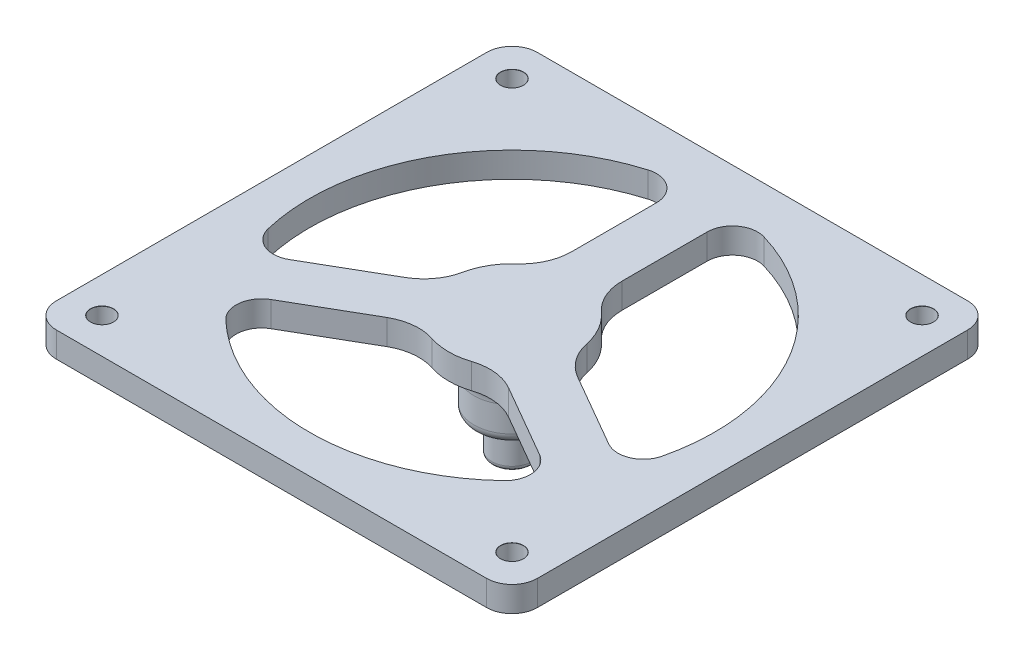
SolidWorks part; units mm, degrees
ref_plane "Front Plane" through (0, 0, 0) normal (0, 0, 1) x (1, 0, 0)
ref_plane "Top Plane" through (0, 0, 0) normal (0, 1, 0) x (1, 0, 0)
ref_plane "Right Plane" through (0, 0, 0) normal (1, 0, 0) x (0, 0, -1)
sketch "Sketch1" plane through (0, 0, 0) normal (0, 1, 0) x (1, 0, 0)
  line L1 (-47.5, -47.5) -> (47.5, -47.5)
  line L2 (-47.5, -47.5) -> (-47.5, 47.5)
  line L3 (-47.5, 47.5) -> (47.5, 47.5)
  line L4 (47.5, -47.5) -> (47.5, 47.5)
  line L5 (-47.5, -47.5) -> (47.5, 47.5) construction
  line L6 (-47.5, 47.5) -> (47.5, -47.5) construction
  point P0 (0, 0)
  dimension "D1" = 95
extrude "Boss-Extrude1" add sketch "Sketch1" along normal blind 5 contours L2 L3 L4 L1
fillet "Fillet1" radius 5 4 edges at (-47.5, 2.5, -47.5) (47.5, 2.5, -47.5) (47.5, 2.5, 47.5) (-47.5, 2.5, 47.5)
sketch "Sketch3" plane through (0, 5, 0) normal (0, 1, 0) x (1, 0, 0)
  line L0 (-47.5, -42.5) -> (-47.5, 42.5) construction
  line L1 (-40.5, -40.5) -> (40.5, -40.5) construction
  line L2 (-40.5, -40.5) -> (-40.5, 40.5) construction
  line L3 (-40.5, 40.5) -> (40.5, 40.5) construction
  line L4 (40.5, -40.5) -> (40.5, 40.5) construction
  line L5 (-40.5, -40.5) -> (40.5, 40.5) construction
  line L6 (-40.5, 40.5) -> (40.5, -40.5) construction
  point P1 (0, 0)
  point P6 (87.598, 42.5)
  dimension "D1" = 7
hole_wizard "M4 Clearance Hole1" positions "3DSketch1" profile "Sketch4" hole size "M4" standard "ANSI Metric" end condition through all
sketch3d "3DSketch1"
  point P0 (-40.5, 5, -40.5)
  point P3 (40.5, 5, -40.5)
  point P6 (40.5, 5, 40.5)
  point P9 (-40.5, 5, 40.5)
sketch "Sketch4" plane through (-40.5, 5, -40.5) normal (1, 0, 0) x (0, 0, 1)
  line L0 (0, 0) -> (0, 5)
  line L1 (0, 5) -> (2.25, 5)
  line L2 (2.25, 5) -> (2.25, 0.025)
  line L3 (2.25, 0.025) -> (2.275, 0)
  line L5 (2.275, 0) -> (0, 0)
  line L6 (-2.25, 0.025) -> (-2.275, 0) construction
  line L11 (0, -6.35) -> (0, 107.95) construction
  dimension "Thru Hole Dia." = 4.5
  dimension "Thru Hole Depth" = 5
  dimension "Near C'Sink Dia." = 4.55
  dimension "Near C'Sink Angle" = 90
sketch "Sketch5" plane through (0, 0, 0) normal (0, -1, 0) x (1, 0, 0)
  circle A0 centre (0, 0) radius 7.5
  dimension "D1" = 15
extrude "Boss-Extrude2" add sketch "Sketch5" along normal blind 12
sketch "Sketch6" plane through (0, -12, 0) normal (0, -1, 0) x (1, 0, 0)
  circle A0 centre (0, 0) radius 4
  dimension "D1" = 8
extrude "Boss-Extrude3" add sketch "Sketch6" along normal blind 7
fillet "Fillet2" radius 2 1 edges at (0, -12, -7.5)
fillet "Fillet3" radius 5 1 edges at (0, 0, 7.5)
fillet "Fillet4" radius 1 1 edges at (0, -19, -4)
sketch "Sketch2" plane through (0, 5, 0) normal (0, 1, 0) x (1, 0, 0)
  line L0 (5, 39.6863) -> (5, 11.4564)
  line L1 (0, 0) -> (0, 40) construction
  line L2 (-5, 39.6863) -> (-5, 11.4564)
  line L3 (-5, 20) -> (5, 20) construction
  line L4 (0, 0) -> (-34.641, -20) construction
  line L5 (-7.4216, -10.0583) -> (-31.8693, -24.1733)
  line L6 (-12.4216, -1.3981) -> (-36.8693, -15.513)
  line L7 (-24.2916, -8.2513) -> (-19.2916, -16.9115) construction
  line L8 (0, 0) -> (34.641, -20) construction
  line L9 (12.4216, -1.3981) -> (36.8693, -15.513)
  line L10 (7.4216, -10.0583) -> (31.8693, -24.1733)
  line L11 (19.9071, -17.2669) -> (24.9071, -8.6066) construction
  arc A0 (36.8693, -15.513) -> (5, 39.6863) centre (0, 0) ccw
  arc A1 (-5, 11.4564) -> (-12.4216, -1.3981) centre (0, 0) ccw
  arc A2 (-7.4216, -10.0583) -> (7.4216, -10.0583) centre (0, 0) ccw
  arc A3 (12.4216, -1.3981) -> (5, 11.4564) centre (0, 0) ccw
  arc A4 (-31.8693, -24.1733) -> (31.8693, -24.1733) centre (0, 0) ccw
  arc A5 (-5, 39.6863) -> (-36.8693, -15.513) centre (0, 0) ccw
  point P1 (36.4674, -16.4008)
  point P11 (0, 20)
  point P19 (-21.7916, -12.5814)
  point P24 (0, 0)
  point P27 (22.4071, -12.9367)
  dimension "D1" = 80
  dimension "D2" = 25
  dimension "D3" = 10
  dimension "D4" = 120
  dimension "D5" = 10
  dimension "D6" = 120
  dimension "D7" = 10
extrude "Cut-Extrude2" cut sketch "Sketch2" against normal up to next
fillet "Fillet5" radius 5 6 edges at (-5, 2.5, -39.6863) (5, 2.5, -39.6863) (31.8693, 2.5, 24.1733) (36.8693, 2.5, 15.513) (-31.8693, 2.5, 24.1733) (-36.8693, 2.5, 15.513)
fillet "Fillet6" radius 10 6 edges at (-7.4216, 2.5, 10.0583) (7.4216, 2.5, 10.0583) (-12.4216, 2.5, 1.3981) (-5, 2.5, -11.4564) (5, 2.5, -11.4564) (12.4216, 2.5, 1.3981)
